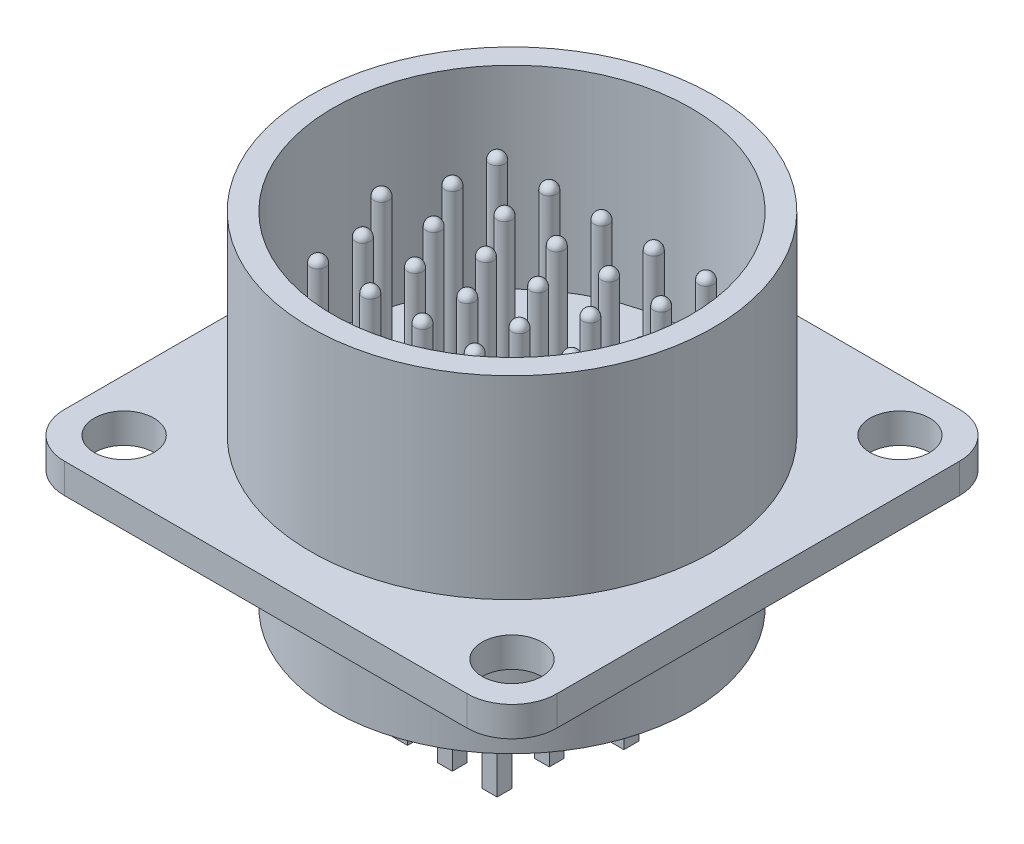
SolidWorks part; units mm, degrees
ref_plane "Спереди" through (0, 0, 0) normal (0, 0, 1) x (1, 0, 0)
ref_plane "Сверху" through (0, 0, 0) normal (0, 1, 0) x (1, 0, 0)
ref_plane "Справа" through (0, 0, 0) normal (1, 0, 0) x (0, 0, -1)
sketch "Эскиз1" plane through (0, 0, 0) normal (0, 1, 0) x (1, 0, 0)
  line L0 (0, 16.5) -> (33, 16.5) construction
  line L1 (3, 0) -> (30, 0)
  line L2 (0, 3) -> (0, 30)
  line L3 (3, 33) -> (30, 33)
  line L4 (33, 3) -> (33, 30)
  line L5 (16.5, 33) -> (16.5, 0) construction
  line L7 (3.5, 29.5) -> (29.5, 29.5) construction
  line L8 (3.5, 29.5) -> (3.5, 3.5) construction
  line L9 (3.5, 3.5) -> (29.5, 3.5) construction
  line L10 (29.5, 29.5) -> (29.5, 3.5) construction
  circle A0 centre (3.5, 29.5) radius 2
  circle A1 centre (29.5, 29.5) radius 2
  circle A2 centre (3.5, 3.5) radius 2
  circle A3 centre (29.5, 3.5) radius 2
  arc A4 (0, 3) -> (3, 0) centre (3, 3) ccw
  arc A5 (33, 3) -> (30, 0) centre (30, 3) cw
  arc A6 (33, 30) -> (30, 33) centre (30, 30) ccw
  arc A7 (3, 33) -> (0, 30) centre (3, 30) ccw
  point P19 (0, 0)
  point P24 (33, 33)
  point P27 (0, 33)
  dimension "D5" = 4
  dimension "D6" = 3
  dimension "D1" = 33
  dimension "D2" = 33
  dimension "D3" = 26
  dimension "D4" = 26
extrude "Бобышка-Вытянуть1" add sketch "Эскиз1" along normal blind 2
sketch "Эскиз2" plane through (0, 2, 0) normal (0, 1, 0) x (1, 0, 0)
  line L0 (0, 16.5) -> (33, 16.5) construction
  line L1 (0, 30) -> (0, 3) construction
  line L2 (33, 3) -> (33, 30) construction
  line L3 (16.5, 33) -> (16.5, 0) construction
  line L4 (30, 33) -> (3, 33) construction
  line L5 (3, 0) -> (30, 0) construction
  circle A0 centre (16.5, 16.5) radius 13.5
  circle A1 centre (16.5, 16.5) radius 12
  dimension "D1" = 27
  dimension "D2" = 24
extrude "Бобышка-Вытянуть2" add sketch "Эскиз2" along normal blind 13
sketch "Эскиз3" plane through (0, 2, 0) normal (0, 1, 0) x (1, 0, 0)
  line L0 (0, 16.5) -> (33, 16.5) construction
  line L1 (0, 30) -> (0, 3) construction
  line L2 (33, 3) -> (33, 30) construction
  line L3 (16.5, 33) -> (16.5, 0) construction
  line L4 (30, 33) -> (3, 33) construction
  line L5 (3, 0) -> (30, 0) construction
  circle A0 centre (7.75, 16.5) radius 0.5
  circle A1 centre (16.5, 19.5) radius 0.5
  circle A2 centre (16.5, 22.5) radius 0.5
  circle A3 centre (16.5, 13.5) radius 0.5
  circle A4 centre (16.5, 10.5) radius 0.5
  circle A5 centre (20, 10.5) radius 0.5
  circle A6 centre (20, 13.5) radius 0.5
  circle A7 centre (18.25, 16.5) radius 0.5
  circle A8 centre (20, 19.5) radius 0.5
  circle A9 centre (20, 22.5) radius 0.5
  circle A10 centre (23.5, 10.5) radius 0.5
  circle A11 centre (23.5, 13.5) radius 0.5
  circle A12 centre (21.75, 16.5) radius 0.5
  circle A13 centre (23.5, 19.5) radius 0.5
  circle A14 centre (23.5, 22.5) radius 0.5
  circle A15 centre (13, 10.5) radius 0.5
  circle A16 centre (13, 13.5) radius 0.5
  circle A17 centre (14.75, 16.5) radius 0.5
  circle A18 centre (13, 19.5) radius 0.5
  circle A19 centre (13, 22.5) radius 0.5
  circle A20 centre (9.5, 10.5) radius 0.5
  circle A21 centre (9.5, 13.5) radius 0.5
  circle A22 centre (11.25, 16.5) radius 0.5
  circle A23 centre (9.5, 19.5) radius 0.5
  circle A24 centre (9.5, 22.5) radius 0.5
  circle A25 centre (25.25, 16.5) radius 0.5
  dimension "D1" = 1
  dimension "D2" = 3
  dimension "D3" = 1.75
  dimension "D4" = 3
  dimension "D5" = 1.75
  dimension "D8" = 3.5
  dimension "D9" = 3.5
  dimension "D10" = 3.5
  dimension "D11" = 3.5
  dimension "D6" = 3
  dimension "D7" = 3
extrude "Бобышка-Вытянуть3" add sketch "Эскиз3" along normal blind 10
sketch "Эскиз4" plane through (0, 0, 0) normal (0, -1, 0) x (1, 0, 0)
  line L0 (0, -16.5) -> (33, -16.5) construction
  line L1 (0, -30) -> (0, -3) construction
  line L2 (33, -3) -> (33, -30) construction
  line L3 (16.5, 0) -> (16.5, -33) construction
  line L4 (3, 0) -> (30, 0) construction
  line L5 (30, -33) -> (3, -33) construction
  circle A0 centre (16.5, -16.5) radius 12
  circle A1 centre (16.5, -16.5) radius 10.5
  dimension "D1" = 24
  dimension "D2" = 21
extrude "Бобышка-Вытянуть4" add sketch "Эскиз4" along normal blind 8
sketch "Эскиз5" plane through (0, 0, 0) normal (0, -1, 0) x (1, 0, 0)
  circle A1 centre (16.5, -16.5) radius 10.5
  circle A2 centre (16.5, -16.5) radius 10.5
  dimension "D1" = 0
extrude "Бобышка-Вытянуть5" add sketch "Эскиз5" along normal blind 4
sketch "Эскиз6" plane through (0, -4, 0) normal (0, -1, 0) x (1, 0, 0)
  line L0 (0, -16.5) -> (33, -16.5) construction
  line L1 (0, -30) -> (0, -3) construction
  line L2 (33, -3) -> (33, -30) construction
  line L3 (16.5, 0) -> (16.5, -33) construction
  line L4 (3, 0) -> (30, 0) construction
  line L5 (30, -33) -> (3, -33) construction
  line L6 (19, -9) -> (19, -10)
  line L11 (16, -12.5) -> (17, -12.5)
  line L12 (16, -12.5) -> (16, -13.5)
  line L13 (16, -13.5) -> (17, -13.5)
  line L14 (17, -12.5) -> (17, -13.5)
  line L15 (16, -9) -> (17, -9)
  line L16 (16, -9) -> (16, -10)
  line L17 (16, -10) -> (17, -10)
  line L18 (17, -9) -> (17, -10)
  line L19 (16, -19.5) -> (17, -19.5)
  line L20 (16, -19.5) -> (16, -20.5)
  line L21 (16, -20.5) -> (17, -20.5)
  line L22 (17, -19.5) -> (17, -20.5)
  line L23 (16, -23) -> (17, -23)
  line L24 (16, -23) -> (16, -24)
  line L25 (16, -24) -> (17, -24)
  line L26 (17, -23) -> (17, -24)
  line L27 (19, -9) -> (20, -9)
  line L28 (20, -9) -> (20, -10)
  line L29 (19, -10) -> (20, -10)
  line L30 (19, -12.5) -> (20, -12.5)
  line L31 (19, -12.5) -> (19, -13.5)
  line L32 (19, -13.5) -> (20, -13.5)
  line L33 (20, -12.5) -> (20, -13.5)
  line L34 (17.5, -16) -> (18.5, -16)
  line L35 (17.5, -16) -> (17.5, -17)
  line L36 (17.5, -17) -> (18.5, -17)
  line L37 (18.5, -16) -> (18.5, -17)
  line L38 (19, -20.5) -> (20, -20.5)
  line L39 (20, -19.5) -> (20, -20.5)
  line L40 (19, -19.5) -> (20, -19.5)
  line L41 (19, -19.5) -> (19, -20.5)
  line L42 (19, -23) -> (20, -23)
  line L43 (19, -23) -> (19, -24)
  line L44 (19, -24) -> (20, -24)
  line L45 (20, -23) -> (20, -24)
  line L46 (22, -9) -> (22, -10)
  line L47 (22, -9) -> (23, -9)
  line L48 (23, -9) -> (23, -10)
  line L49 (22, -10) -> (23, -10)
  line L50 (22, -12.5) -> (23, -12.5)
  line L51 (22, -12.5) -> (22, -13.5)
  line L52 (22, -13.5) -> (23, -13.5)
  line L53 (23, -12.5) -> (23, -13.5)
  line L54 (20.5, -16) -> (21.5, -16)
  line L55 (20.5, -16) -> (20.5, -17)
  line L56 (20.5, -17) -> (21.5, -17)
  line L57 (21.5, -16) -> (21.5, -17)
  line L58 (22, -20.5) -> (23, -20.5)
  line L59 (23, -19.5) -> (23, -20.5)
  line L60 (22, -19.5) -> (23, -19.5)
  line L61 (22, -19.5) -> (22, -20.5)
  line L62 (22, -23) -> (23, -23)
  line L63 (22, -23) -> (22, -24)
  line L64 (22, -24) -> (23, -24)
  line L65 (23, -23) -> (23, -24)
  line L66 (-3, -16.5) -> (30, -16.5) construction
  line L67 (13, -9) -> (13, -10)
  line L68 (13, -9) -> (14, -9)
  line L69 (14, -9) -> (14, -10)
  line L70 (13, -10) -> (14, -10)
  line L71 (13, -12.5) -> (14, -12.5)
  line L72 (13, -12.5) -> (13, -13.5)
  line L73 (13, -13.5) -> (14, -13.5)
  line L74 (14, -12.5) -> (14, -13.5)
  line L75 (15.5, -16) -> (15.5, -17)
  line L76 (14.5, -16) -> (15.5, -16)
  line L77 (14.5, -17) -> (15.5, -17)
  line L78 (14.5, -16) -> (14.5, -17)
  line L79 (13, -19.5) -> (14, -19.5)
  line L80 (13, -19.5) -> (13, -20.5)
  line L81 (14, -19.5) -> (14, -20.5)
  line L82 (13, -20.5) -> (14, -20.5)
  line L83 (13, -23) -> (14, -23)
  line L84 (13, -24) -> (14, -24)
  line L85 (14, -23) -> (14, -24)
  line L86 (13, -23) -> (13, -24)
  line L87 (-6, -16.5) -> (27, -16.5) construction
  line L88 (10, -9) -> (10, -10)
  line L89 (10, -9) -> (11, -9)
  line L90 (11, -9) -> (11, -10)
  line L91 (10, -10) -> (11, -10)
  line L92 (10, -12.5) -> (11, -12.5)
  line L93 (10, -12.5) -> (10, -13.5)
  line L94 (10, -13.5) -> (11, -13.5)
  line L95 (11, -12.5) -> (11, -13.5)
  line L96 (12.5, -16) -> (12.5, -17)
  line L97 (11.5, -16) -> (12.5, -16)
  line L98 (11.5, -17) -> (12.5, -17)
  line L99 (11.5, -16) -> (11.5, -17)
  line L100 (10, -19.5) -> (11, -19.5)
  line L101 (10, -19.5) -> (10, -20.5)
  line L102 (11, -19.5) -> (11, -20.5)
  line L103 (10, -20.5) -> (11, -20.5)
  line L104 (10, -23) -> (11, -23)
  line L105 (10, -24) -> (11, -24)
  line L106 (11, -23) -> (11, -24)
  line L107 (10, -23) -> (10, -24)
  line L109 (8.5, -16) -> (9.5, -16)
  line L110 (8.5, -16) -> (8.5, -17)
  line L111 (8.5, -17) -> (9.5, -17)
  line L112 (9.5, -16) -> (9.5, -17)
  line L113 (23.5, -16) -> (24.5, -16)
  line L114 (23.5, -16) -> (23.5, -17)
  line L115 (23.5, -17) -> (24.5, -17)
  line L116 (24.5, -16) -> (24.5, -17)
  dimension "D2" = 2.5
  dimension "D3" = 1
  dimension "D4" = 1
  dimension "D5" = 2.5
  dimension "D7" = 1
  dimension "D8" = 1
  dimension "D9" = 2
  dimension "D10" = 2
  dimension "D11" = 2
  dimension "D12" = 2
  dimension "D13" = 2
  dimension "D14" = 1
  dimension "D6" = 2
  dimension "D15" = 2
extrude "Бобышка-Вытянуть6" add sketch "Эскиз6" along normal blind 8
fillet "Скругление3" radius 0.5 26 edges at (23.5, 12, -13) (23.5, 12, -22) (25.25, 12, -16) (23.5, 12, -19) (20, 12, -22) (20, 12, -19) (21.75, 12, -16) (23.5, 12, -10) (20, 12, -10) (20, 12, -13) (18.25, 12, -16) (16.5, 12, -13) (16.5, 12, -10) (13, 12, -10) (9.5, 12, -10) (13, 12, -13) (14.75, 12, -16) (16.5, 12, -19) (16.5, 12, -22) (13, 12, -22) (13, 12, -19) (11.25, 12, -16) (9.5, 12, -13) (7.75, 12, -16) (9.5, 12, -19) (9.5, 12, -22)
